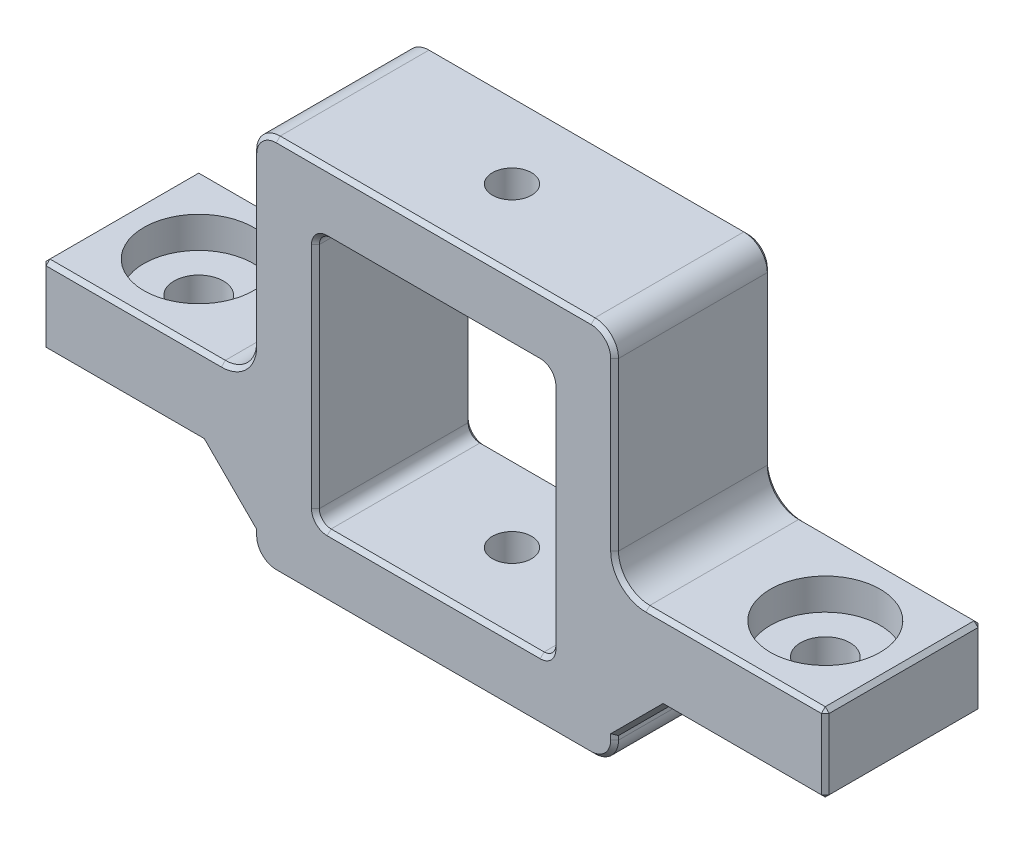
SolidWorks part; units mm, degrees
ref_plane "Front Plane" through (0, 0, 0) normal (0, 0, 1) x (1, 0, 0)
ref_plane "Top Plane" through (0, 0, 0) normal (0, 1, 0) x (1, 0, 0)
ref_plane "Right Plane" through (0, 0, 0) normal (1, 0, 0) x (0, 0, -1)
sketch "Sketch1" plane through (0, 0, 0) normal (0, 0, 1) x (1, 0, 0)
  line L0 (-50, -14.2) -> (-29.5, -14.2)
  line L1 (-15.1, -16.1) -> (15.1, -16.1)
  line L2 (-15.1, -16.1) -> (-15.1, 16.1)
  line L3 (-15.1, 16.1) -> (15.1, 16.1)
  line L4 (15.1, -16.1) -> (15.1, 16.1)
  line L5 (-15.1, -16.1) -> (15.1, 16.1) construction
  line L6 (-15.1, 16.1) -> (15.1, -16.1) construction
  line L7 (-50, -14.2) -> (-50, 24.1)
  line L8 (-50, 24.1) -> (50, 24.1)
  line L9 (-29.5, -14.2) -> (-23.1, -20.6)
  line L10 (-23.1, -20.6) -> (-23.1, -24.1)
  line L11 (-23.1, -24.1) -> (23.1, -24.1)
  line L12 (23.1, -24.1) -> (23.1, -20.6)
  line L13 (23.1, -20.6) -> (29.5, -14.2)
  line L14 (29.5, -14.2) -> (50, -14.2)
  line L15 (50, -14.2) -> (50, 24.1)
  point P0 (0, 0)
  dimension "D1" = 32.2
  dimension "D2" = 30.2
  dimension "D3" = 30.3
  dimension "D4" = 50
  dimension "D5" = 20.5
  dimension "D6" = 8
  dimension "D7" = 8
  dimension "D8" = 8
  dimension "D9" = 90
  dimension "D10" = 8
  dimension "D11" = 38.3
  dimension "D12" = 100
extrude "Boss-Extrude1" add sketch "Sketch1" along normal mid plane 20
fillet "Fillet1" radius 1.5 4 edges at (-15.1, -16.1, 0) (15.1, -16.1, 0) (15.1, 16.1, 0) (-15.1, 16.1, 0)
sketch "Sketch3" plane through (0, 24.1, 0) normal (0, 1, 0) x (1, 0, 0)
  line L0 (0, 0) -> (40, 0) construction
  line L1 (0, 0) -> (-40, 0) construction
  circle A0 centre (-40, 0) radius 3.15
  circle A1 centre (40, 0) radius 3.15
  dimension "D1" = 6.3
  dimension "D2" = 40
extrude "Cut-Extrude1" cut sketch "Sketch3" against normal through all
sketch "Sketch6" plane through (0, 0, 10) normal (0, 0, 1) x (1, 0, 0)
  line L0 (-15.1, 14.6) -> (-15.1, -14.6) construction
  line L1 (-76.9, 52.4) -> (-23.1, 52.4)
  line L2 (-76.9, 52.4) -> (-76.9, -4.2)
  line L3 (-76.9, -4.2) -> (-23.1, -4.2)
  line L4 (-23.1, 52.4) -> (-23.1, -4.2)
  line L5 (-76.9, 52.4) -> (-23.1, -4.2) construction
  line L6 (-76.9, -4.2) -> (-23.1, 52.4) construction
  line L7 (76.9, 52.4) -> (23.1, 52.4)
  line L8 (76.9, 52.4) -> (76.9, -4.2)
  line L9 (76.9, -4.2) -> (23.1, -4.2)
  line L10 (23.1, 52.4) -> (23.1, -4.2)
  line L11 (76.9, 52.4) -> (23.1, -4.2) construction
  line L12 (76.9, -4.2) -> (23.1, 52.4) construction
  line L13 (15.1, -14.6) -> (15.1, 14.6) construction
  line L14 (-50, -14.2) -> (-29.5, -14.2) construction
  point P0 (-50, 24.1)
  point P6 (50, 24.1)
  dimension "D1" = 8
  dimension "D2" = 8
  dimension "D3" = 10
extrude "Cut-Extrude4" cut sketch "Sketch6" against normal through all
sketch "Sketch4" plane through (0, 24.1, 0) normal (0, 1, 0) x (1, 0, 0)
  circle A0 centre (-40, 0) radius 7
  circle A1 centre (40, 0) radius 7
  dimension "D1" = 14
extrude "Cut-Extrude2" cut sketch "Sketch4" against normal offset from surface (32.3 mm away) 6 up to face at (-40, -14.2, 3.15)
fillet "Fillet2" radius 3 4 edges at (23.1, -24.1, 0) (-23.1, -24.1, 0) (23.1, 24.1, 0) (-23.1, 24.1, 0)
fillet "Fillet3" radius 4 2 edges at (23.1, -4.2, 0) (-23.1, -4.2, 0)
chamfer "Chamfer1" distance 0.5 angle 45 60 edges at (-14.6607, 15.6607, -10) (0, 16.1, -10) (14.6607, 15.6607, -10) (15.1, 0, -10) (14.6607, -15.6607, -10) (0, -16.1, -10) (-14.6607, -15.6607, -10) (-15.1, 0, -10) (14.6607, 15.6607, 10) (0, 16.1, 10) (-14.6607, 15.6607, 10) (-15.1, 0, 10) (-14.6607, -15.6607, 10) (0, -16.1, 10) (14.6607, -15.6607, 10) (15.1, 0, 10) (50, -14.2, 0) (26.3, -17.4, -10) (39.75, -14.2, -10) (50, -9.2, -10) (0, 24.1, -10) (-50, -9.2, -10) (23.1, -20.85, -10) (22.2213, -23.2213, -10) (0, -24.1, -10) (-22.2213, -23.2213, -10) (-23.1, -20.85, -10) (-26.3, -17.4, -10) (-39.75, -14.2, -10) (-50, -14.2, 0) (-22.2213, -23.2213, 10) (-23.1, -20.85, 10) (-26.3, -17.4, 10) (-39.75, -14.2, 10) (-50, -9.2, 10) (0, 24.1, 10) (50, -9.2, 10) (39.75, -14.2, 10) (26.3, -17.4, 10) (23.1, -20.85, 10) (22.2213, -23.2213, 10) (0, -24.1, 10) (50, -4.2, 0) (38.55, -4.2, -10) (23.1, 10.45, -10) (-23.1, 10.45, -10) (-38.55, -4.2, -10) (-50, -4.2, 0) (-38.55, -4.2, 10) (-23.1, 10.45, 10) (23.1, 10.45, 10) (38.55, -4.2, 10) (24.2716, -3.0284, -10) (-24.2716, -3.0284, -10) (-24.2716, -3.0284, 10) (24.2716, -3.0284, 10) (-22.2213, 23.2213, -10) (22.2213, 23.2213, -10) (-22.2213, 23.2213, 10) (22.2213, 23.2213, 10)
sketch "Sketch5" plane through (0, 24.1, 0) normal (0, 1, 0) x (1, 0, 0)
  circle A0 centre (0, 0) radius 2.5
  dimension "D1" = 5
extrude "Cut-Extrude3" cut sketch "Sketch5" against normal through all
